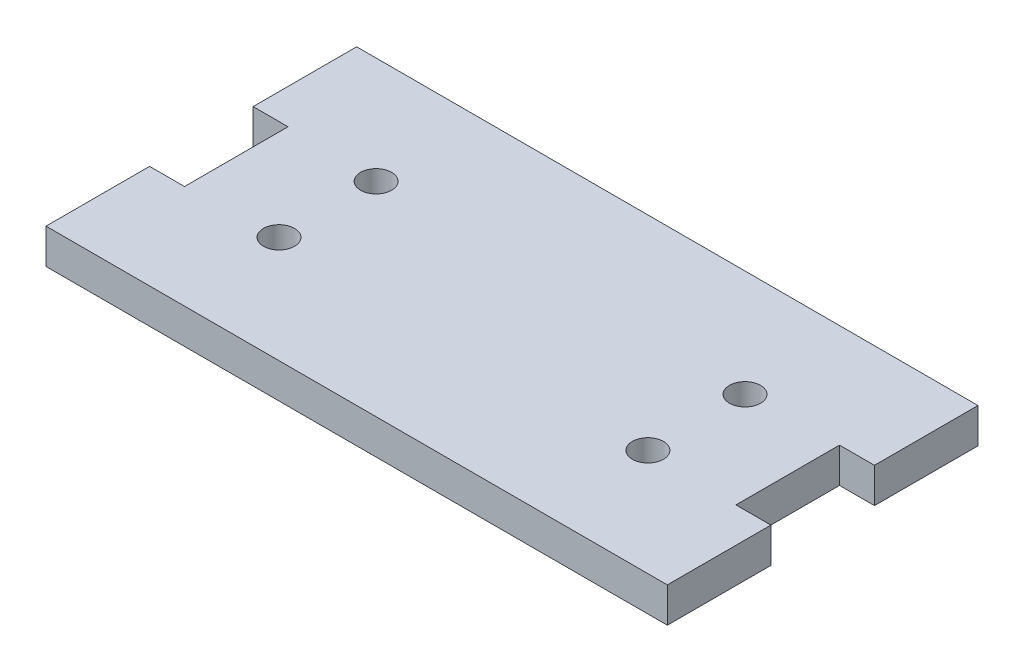
SolidWorks part; units mm, degrees
ref_plane "Front Plane" through (0, 0, 0) normal (0, 0, 1) x (1, 0, 0)
ref_plane "Top Plane" through (0, 0, 0) normal (0, 1, 0) x (1, 0, 0)
ref_plane "Right Plane" through (0, 0, 0) normal (1, 0, 0) x (0, 0, -1)
sketch "Sketch1" plane through (0, 0, 0) normal (0, 1, 0) x (1, 0, 0)
  line L0 (80, 80) -> (80, 0) construction
  line L1 (0, 0) -> (160, 0)
  line L2 (0, 0) -> (0, 80)
  line L3 (0, 80) -> (160, 80)
  line L4 (160, 0) -> (160, 80)
  line L5 (0, 40) -> (160, 40) construction
  line L6 (8.8542, 80) -> (8.8542, 53.3333) construction
  line L7 (9, 80) -> (0, 80)
  line L8 (9, 80) -> (9, 0)
  line L9 (9, 0) -> (0, 0)
  line L10 (0, 80) -> (0, 0)
  line L11 (8.8542, 53.3333) -> (8.8542, 26.6667) construction
  line L12 (0, 53.3333) -> (9, 53.3333)
  line L13 (0, 53.3333) -> (0, 26.6667)
  line L14 (0, 26.6667) -> (9, 26.6667)
  line L15 (9, 53.3333) -> (9, 26.6667)
  line L16 (8.8542, 26.6667) -> (8.8542, 0) construction
  line L17 (151.1458, 26.6667) -> (151.1458, 0) construction
  line L18 (151.1458, 53.3333) -> (151.1458, 26.6667) construction
  line L19 (151.1458, 80) -> (151.1458, 53.3333) construction
  line L20 (151, 53.3333) -> (151, 26.6667)
  line L21 (160, 26.6667) -> (151, 26.6667)
  line L22 (160, 53.3333) -> (160, 26.6667)
  line L23 (160, 53.3333) -> (151, 53.3333)
  line L24 (160, 80) -> (160, 0)
  line L25 (151, 0) -> (160, 0)
  line L26 (151, 80) -> (151, 0)
  line L27 (151, 80) -> (160, 80)
  line L28 (160, 0) -> (160, 80)
  circle A2 centre (32.5, 52.5) radius 4
  circle A3 centre (32.5, 27.5) radius 4
  circle A4 centre (127.5, 27.5) radius 4
  circle A5 centre (127.5, 52.5) radius 4
  dimension "D4" = 8
  dimension "D1" = 160
  dimension "D2" = 80
  dimension "D3" = 9
  dimension "D5" = 47.5
  dimension "D6" = 12.5
extrude "Boss-Extrude1" add sketch "Sketch1" along normal blind 9 contours L26 L3 L8 L1 L20 A2 A3 | L10 L12 L8 L3 | L14 L2 L1 L8 | L3 L26 L23 L4 | L21 L26 L1 L4
equation "\"D5@Sketch1\"=95/2"
equation "\"D6@Sketch1\"=12.5"
